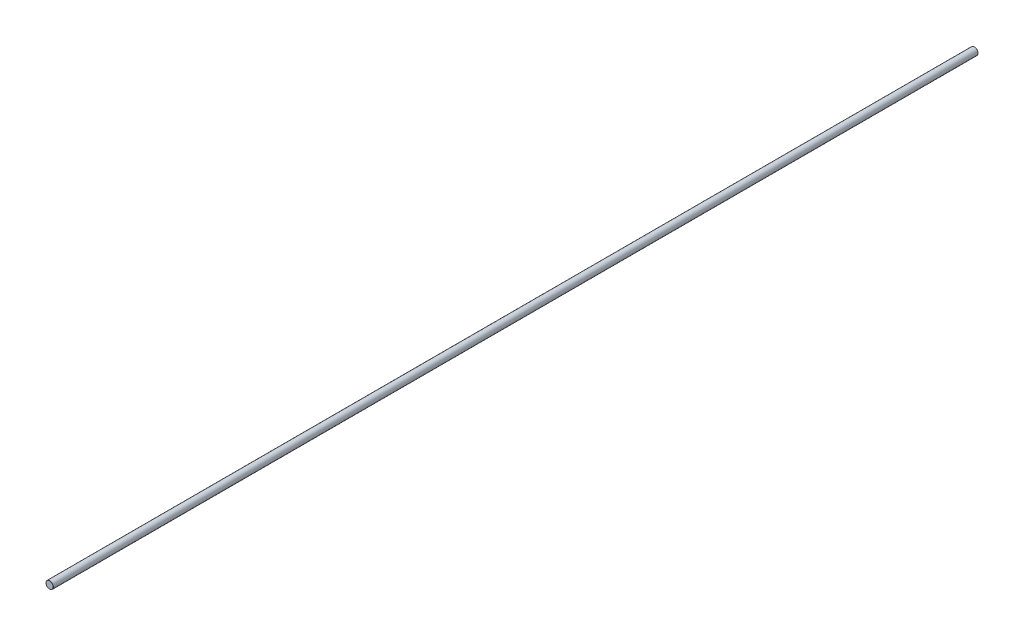
SolidWorks part; units mm, degrees
ref_plane "Front Plane" through (0, 0, 0) normal (0, 0, 1) x (1, 0, 0)
ref_plane "Top Plane" through (0, 0, 0) normal (0, 1, 0) x (1, 0, 0)
ref_plane "Right Plane" through (0, 0, 0) normal (1, 0, 0) x (0, 0, -1)
sketch "Sketch1" plane through (0, 0, 0) normal (0, 0, 1) x (1, 0, 0)
  circle A0 centre (0, 0) radius 6 construction
  dimension "Diameter" = 12
sketch "Sketch2" plane through (0, 0, 0) normal (1, 0, 0) x (0, 0, -1)
  line L0 (750, 0) -> (-750, 0) construction
  point P0 (-600, 0)
  point P3 (0, 0)
  point P4 (600, 0)
  point P6 (-525, 0)
  point P7 (525, 0)
  dimension "Length" = 1500
  dimension "D1" = 150
  dimension "D2" = 150
  dimension "D3" = 225
  dimension "D4" = 225
sketch "Sketch3" plane through (0, 0, 0) normal (0, 0, 1) x (1, 0, 0)
  circle A0 centre (0, 0) radius 6 construction
  circle A1 centre (0, 0) radius 6
extrude "Boss-Extrude1" add sketch "Sketch3" along normal up to vertex (750 mm away) and the other way up to vertex (750 mm away) up to point (0, 0, 750) other way up to point (0, 0, -750)
chamfer "Chamfer1" distance 0.24 angle 45 2 edges at (6, 0, 750) (6, 0, -750)
ref_plane "Plane1" through (6, 0, 0) normal (1, 0, 0) x (0, 0, -1)
sketch "Sketch5" plane through (0, 0, 0) normal (0, 1, 0) x (1, 0, 0)
  circle A0 centre (0, 0) radius 0.0411
extrude "Cut-Extrude2" cut sketch "Sketch5" against normal through all
equation "\"D1@Chamfer1\"=\"Diameter@Sketch1\"*.02"
equation "\"D1@Sketch2\"=\"D2@Sketch2\""
equation "\"D2@Sketch2\"=\"Length@Sketch2\"*.1"
equation "\"D3@Sketch2\"=\"Length@Sketch2\"*.15"
equation "\"D4@Sketch2\"=\"D3@Sketch2\""
